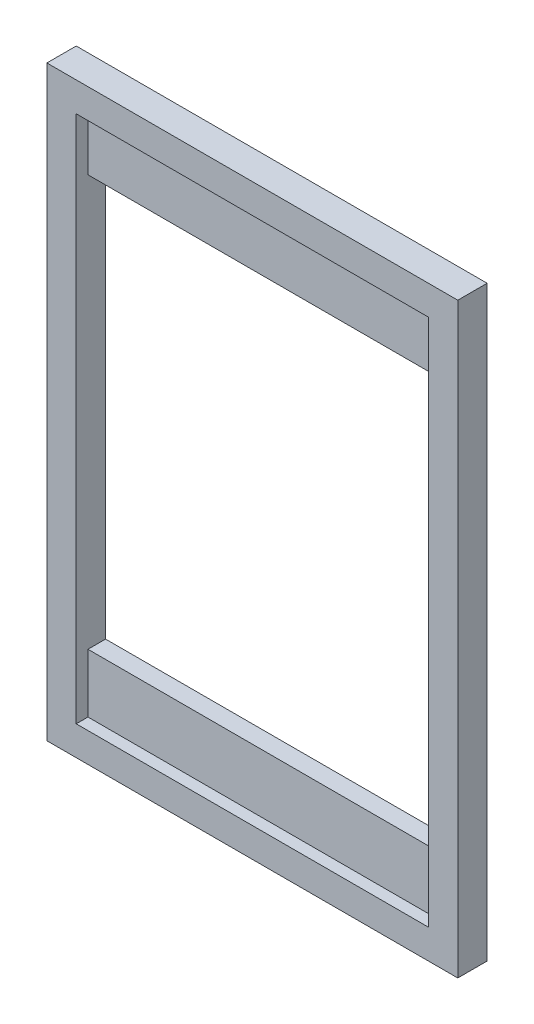
SolidWorks part; units mm, degrees
ref_plane "Front Plane" through (0, 0, 0) normal (1, 0, 0) x (0, 1, 0)
ref_plane "Top Plane" through (0, 0, 0) normal (0, 0, 1) x (0, 1, 0)
ref_plane "Right Plane" through (0, 0, 0) normal (0, 1, 0) x (-1, 0, 0)
sketch "Sketch1" plane through (0, 0, 0) normal (0, 0, 1) x (0, 1, 0)
  line L1 (-50, -35) -> (50, -35)
  line L2 (-50, -35) -> (-50, 35)
  line L3 (-50, 35) -> (50, 35)
  line L4 (50, -35) -> (50, 35)
  line L5 (-50, -35) -> (50, 35) construction
  line L6 (-50, 35) -> (50, -35) construction
  point P0 (0, 0)
  dimension "D1" = 100
  dimension "D2" = 70
extrude "Boss-Extrude1" add sketch "Sketch1" along normal blind 5
sketch "Sketch2" plane through (0, 0, 5) normal (0, 0, 1) x (1, 0, 0)
  line L1 (-30, -45) -> (30, -45)
  line L2 (-30, -45) -> (-30, 45)
  line L3 (-30, 45) -> (30, 45)
  line L4 (30, -45) -> (30, 45)
  line L5 (-30, -45) -> (30, 45) construction
  line L6 (-30, 45) -> (30, -45) construction
  line L8 (35, 50) -> (-35, 50) construction
  line L9 (35, -50) -> (35, 50) construction
  point P0 (0, 0)
  dimension "D1" = 5
  dimension "D2" = 5
  dimension "D3" = 60
  dimension "D4" = 90
extrude "Cut-Extrude1" cut sketch "Sketch2" against normal through all contours L3 L4 L1 L2
sketch "Sketch4" plane through (0, 45, 0) normal (0, -1, 0) x (1, 0, 0)
  line L0 (-35, 5) -> (-35, 0) construction
  line L1 (-30, 3) -> (30, 3)
  line L2 (-30, 3) -> (-30, 0)
  line L3 (-30, 0) -> (30, 0)
  line L4 (30, 3) -> (30, 0)
  line L5 (-30, 3) -> (30, 0) construction
  line L6 (-30, 0) -> (30, 3) construction
  line L7 (35, 5) -> (35, 0) construction
  line L8 (-35, 0) -> (35, 0) construction
  point P0 (0, 1.5)
  dimension "D1" = 5
  dimension "D2" = 5
  dimension "D3" = 3
  dimension "D4" = 0
extrude "Boss-Extrude2" add sketch "Sketch4" along normal blind 10 contours L1 L4 L3 L2
sketch "Sketch5" plane through (-45, -45, 0) normal (0, 1, 0) x (1, 0, 0)
  line L0 (10, 0) -> (80, 0) construction
  line L1 (15, 0) -> (75, 0)
  line L2 (15, 0) -> (15, -3)
  line L3 (15, -3) -> (75, -3)
  line L4 (75, 0) -> (75, -3)
  line L5 (15, 0) -> (75, -3) construction
  line L6 (15, -3) -> (75, 0) construction
  line L10 (80, -5) -> (80, 0) construction
  line L11 (10, -5) -> (10, 0) construction
  point P0 (45, -1.5)
  dimension "D1" = 0
  dimension "D2" = 5
  dimension "D3" = 3
  dimension "D4" = 5
extrude "Boss-Extrude3" add sketch "Sketch5" along normal blind 10 contours L1 L4 L3 L2
